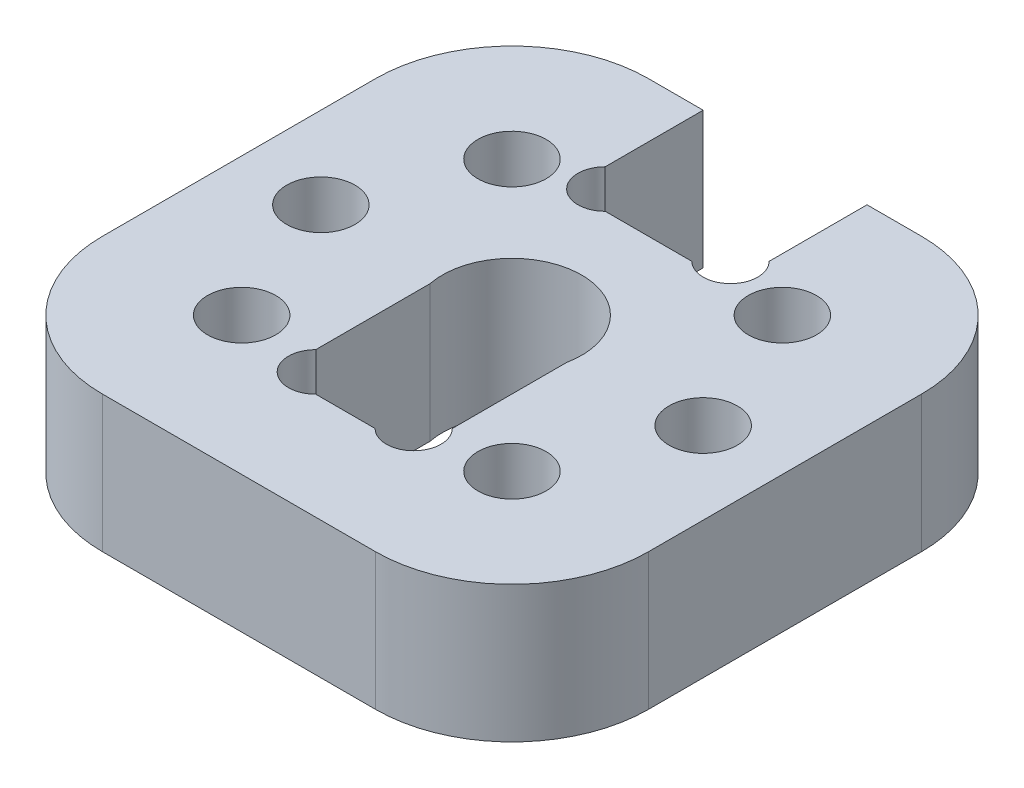
SolidWorks part; units mm, degrees
ref_plane "정면" through (0, 0, 0) normal (0, 0, 1) x (1, 0, 0)
ref_plane "윗면" through (0, 0, 0) normal (0, 1, 0) x (1, 0, 0)
ref_plane "우측면" through (0, 0, 0) normal (1, 0, 0) x (0, 0, -1)
sketch "스케치1" plane through (0, 0, 0) normal (0, 1, 0) x (1, 0, 0)
  line L1 (-10, -10) -> (10, -10)
  line L2 (-10, -10) -> (-10, 10)
  line L3 (-10, 10) -> (10, 10)
  line L4 (10, -10) -> (10, 10)
  line L5 (-10, -10) -> (10, 10) construction
  line L6 (-10, 10) -> (10, -10) construction
  point P0 (0, 0)
  dimension "D1" = 20
extrude "보스-돌출1" add sketch "스케치1" along normal blind 5
sketch "스케치2" plane through (0, 5, 0) normal (0, 1, 0) x (1, 0, 0)
  circle A0 centre (0, 0) radius 2.55
  dimension "D1" = 5.1
extrude "컷-돌출1" cut sketch "스케치2" against normal blind 5
sketch "스케치3" plane through (0, 0, 0) normal (0, -1, 0) x (1, 0, 0)
  line L0 (2.5, 6.1) -> (2.5, 2.5) construction
  line L1 (-2.5, 6.1) -> (2.5, 6.1)
  line L2 (-2.5, 6.1) -> (-2.5, 0)
  line L3 (-2.5, 0) -> (2.5, 0)
  line L4 (2.5, 6.1) -> (2.5, 0)
extrude "컷-돌출2" cut sketch "스케치3" against normal blind 5
sketch "스케치4" plane through (0, 0, 0) normal (0, -1, 0) x (1, 0, 0)
  line L0 (2.5, 6.1) -> (1.7929, 5.3929) construction
  line L1 (-2.5, 6.1) -> (-1.7929, 5.3929) construction
  line L2 (2.5, 6.1) -> (-2.5, 6.1) construction
  circle A0 centre (1.7929, 5.3929) radius 1
  circle A1 centre (-1.7929, 5.3929) radius 1
  dimension "D3" = 2
  dimension "D1" = 45
  dimension "D2" = 45
sketch "스케치5" plane through (0, 0, 0) normal (0, -1, 0) x (-1, 0, 0)
  line L0 (-2.5, -6.1) -> (-1.7929, -5.3929) construction
  line L1 (2.5, -6.1) -> (1.7929, -5.3929) construction
  line L2 (-2.5, -6.1) -> (2.5, -6.1) construction
  circle A0 centre (-1.7929, -5.3929) radius 1
  circle A1 centre (1.7929, -5.3929) radius 1
  dimension "D3" = 2
  dimension "D1" = 45
  dimension "D2" = 45
extrude "컷-돌출4" cut sketch "스케치5" against normal blind 10
fillet "필렛1" radius 5 4 edges at (10, 2.5, -10) (-10, 2.5, -10) (-10, 2.5, 10) (10, 2.5, 10)
extrude "컷-돌출3" [suppressed] cut sketch "스케치4" against normal blind 5
sketch "스케치6" plane through (0, 0, 0) normal (0, -1, 0) x (1, 0, 0)
  line L0 (5, -10) -> (-5, -10) construction
  line L1 (-3, -5) -> (3, -5)
  line L2 (-3, -5) -> (-3, -10)
  line L3 (-3, -10) -> (3, -10)
  line L4 (3, -5) -> (3, -10)
  dimension "D1" = 5
extrude "컷-돌출5" cut sketch "스케치6" against normal blind 10
sketch "스케치7" plane through (0, 0, 0) normal (0, -1, 0) x (-1, 0, 0)
  line L0 (-3, 5) -> (-2.2929, 5.7071) construction
  line L1 (3, 5) -> (2.2929, 5.7071) construction
  line L2 (-3, 5) -> (3, 5) construction
  circle A0 centre (-2.2929, 5.7071) radius 1
  circle A1 centre (2.2929, 5.7071) radius 1
  dimension "D3" = 2
  dimension "D1" = 45
  dimension "D2" = 45
extrude "컷-돌출6" cut sketch "스케치7" against normal blind 10
sketch "스케치8" plane through (0, 0, 0) normal (0, -1, 0) x (1, 0, 0)
  line L0 (4.9497, 4.9497) -> (0, 0) construction
  line L1 (0, 0) -> (0, 7) construction
  circle A0 centre (0, 0) radius 7 construction
  circle A1 centre (4.9497, 4.9497) radius 1.25
  circle A2 centre (7, 0) radius 1.25
  circle A3 centre (4.9497, -4.9497) radius 1.25
  circle A5 centre (-4.9497, -4.9497) radius 1.25
  circle A6 centre (-7, 0) radius 1.25
  circle A7 centre (-4.9497, 4.9497) radius 1.25
  circle A9 centre (0, 7) radius 1.25 [skipped]
  circle A10 centre (0, -7) radius 1.25 [skipped]
  point P23 (0, 0)
  dimension "D1" = 2.5
  dimension "D2" = 45
  dimension "D3" = 8
extrude "컷-돌출7" cut sketch "스케치8" against normal blind 5
